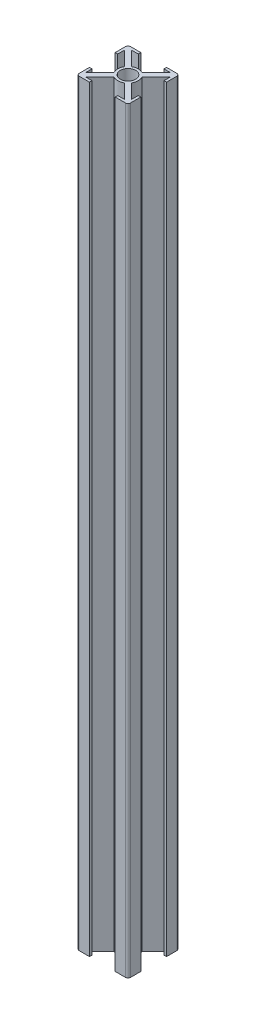
SolidWorks part; units mm, degrees
ref_plane "Plan de face" through (0, 0, 0) normal (0, 0, 1) x (1, 0, 0)
ref_plane "Plan de dessus" through (0, 0, 0) normal (0, 1, 0) x (1, 0, 0)
ref_plane "Plan de droite" through (0, 0, 0) normal (1, 0, 0) x (0, 0, -1)
sketch "Esquisse1" plane through (0, 0, 0) normal (0, 1, 0) x (1, 0, 0)
  line L0 (-9, 7.5858) -> (-3.4457, 2.0315)
  line L1 (-10, 10) -> (-5, 10)
  line L2 (-10, 10) -> (-10, 5)
  line L3 (-10, -10) -> (-5, -10)
  line L4 (10, 10) -> (10, 5)
  line L5 (-7.5858, 9) -> (-2.0315, 3.4457)
  line L6 (2.0315, 3.4457) -> (7.5858, 9)
  line L7 (3.4457, 2.0315) -> (9, 7.5858)
  line L8 (-3.4457, -2.0315) -> (-9, -7.5858)
  line L9 (-2.0315, -3.4457) -> (-7.5858, -9)
  line L10 (2.0315, -3.4457) -> (7.5858, -9)
  line L11 (9, -7.5858) -> (3.4457, -2.0315)
  line L12 (-10, 10) -> (10, -10) construction
  line L13 (-10, -10) -> (10, 10) construction
  line L14 (-7.5858, 9) -> (-5, 9)
  line L15 (9, 7.5858) -> (9, 5)
  line L16 (7.5858, -9) -> (5, -9)
  line L17 (-9, -7.5858) -> (-9, -5)
  line L18 (-5, 10) -> (-5, 9)
  line L19 (5, 9) -> (5, 10)
  line L20 (9, 5) -> (10, 5)
  line L21 (9, -5) -> (10, -5)
  line L22 (-9, -5) -> (-10, -5)
  line L23 (-9, 5) -> (-10, 5)
  line L24 (-5, -9) -> (-5, -10)
  line L25 (5, -9) -> (5, -10)
  line L26 (-10, -5) -> (-10, -10)
  line L27 (-9, 5) -> (-9, 7.5858)
  line L28 (5, 10) -> (10, 10)
  line L29 (5, 9) -> (7.5858, 9)
  line L30 (10, -5) -> (10, -10)
  line L31 (9, -5) -> (9, -7.5858)
  line L32 (-5, -9) -> (-7.5858, -9)
  line L33 (5, -10) -> (10, -10)
  circle A0 centre (0, 0) radius 3
  arc A1 (-2.0315, -3.4457) -> (2.0315, -3.4457) centre (0, 0) ccw
  arc A2 (3.4457, -2.0315) -> (3.4457, 2.0315) centre (0, 0) ccw
  arc A3 (2.0315, 3.4457) -> (-2.0315, 3.4457) centre (0, 0) ccw
  arc A4 (-3.4457, 2.0315) -> (-3.4457, -2.0315) centre (0, 0) ccw
  dimension "D5" = 6
  dimension "D29" = 8
  dimension "D1" = 10
  dimension "D2" = 10
  dimension "D3" = 10
  dimension "D4" = 10
  dimension "D6" = 2
  dimension "D7" = 2
  dimension "D8" = 2
  dimension "D9" = 2
  dimension "D10" = 1
  dimension "D11" = 1
  dimension "D12" = 1
  dimension "D13" = 1
  dimension "D14" = 1
  dimension "D15" = 1
  dimension "D16" = 1
  dimension "D17" = 1
  dimension "D18" = 5
  dimension "D19" = 5
  dimension "D20" = 5
  dimension "D21" = 5
  dimension "D22" = 5
  dimension "D23" = 5
  dimension "D24" = 5
  dimension "D25" = 5
  dimension "D26" = 1
  dimension "D27" = 1
  dimension "D28" = 1
extrude "Boss.-Extru.1" add sketch "Esquisse1" along normal blind 295
fillet "Congé1" radius 1 4 edges at (10, 147.5, -10) (-10, 147.5, -10) (-10, 147.5, 10) (10, 147.5, 10)
